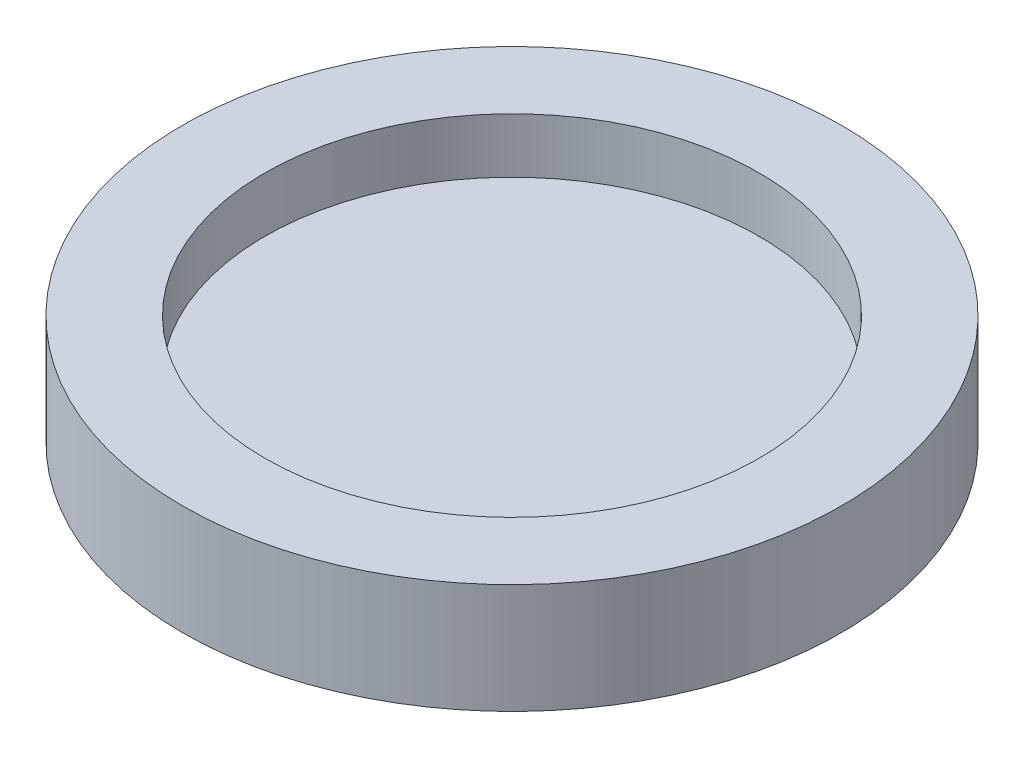
SolidWorks part; units mm, degrees
ref_plane "Front Plane" through (0, 0, 0) normal (0, 0, 1) x (1, 0, 0)
ref_plane "Top Plane" through (0, 0, 0) normal (0, 1, 0) x (1, 0, 0)
ref_plane "Right Plane" through (0, 0, 0) normal (1, 0, 0) x (0, 0, -1)
sketch "Sketch1" plane through (0, 0, 0) normal (0, 1, 0) x (1, 0, 0)
  circle A0 centre (0, 0) radius 60
  dimension "D1" = 120
extrude "Boss-Extrude1" add sketch "Sketch1" against normal blind 20
sketch "Sketch2" plane through (0, 0, 0) normal (0, 1, 0) x (1, 0, 0)
  circle A0 centre (0, 0) radius 45
  dimension "D1" = 90
extrude "Cut-Extrude1" cut sketch "Sketch2" against normal blind 10
